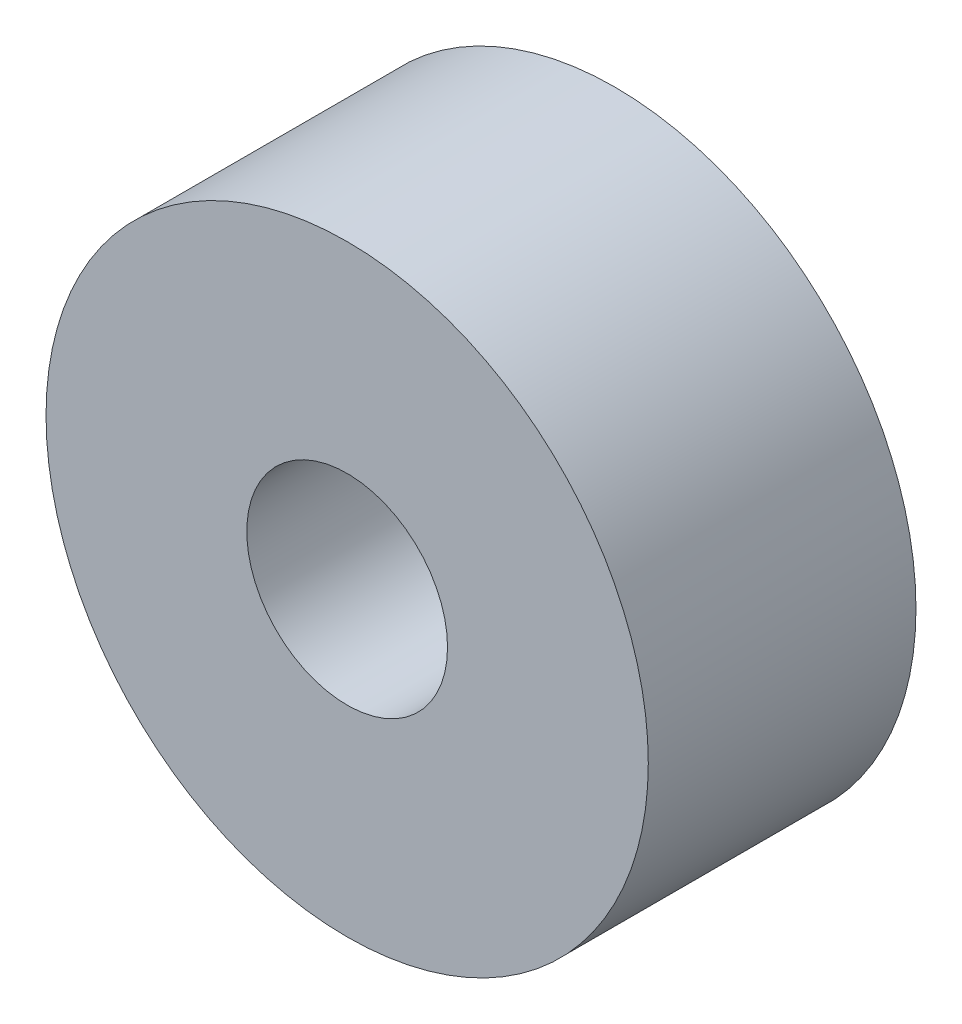
SolidWorks part; units mm, degrees
material "6061 合金"
ref_plane "前视基准面" through (0, 0, 0) normal (0, 0, 1) x (1, 0, 0)
ref_plane "上视基准面" through (0, 0, 0) normal (0, 1, 0) x (1, 0, 0)
ref_plane "右视基准面" through (0, 0, 0) normal (1, 0, 0) x (0, 0, -1)
sketch "草图1" plane through (0, 0, 0) normal (0, 0, 1) x (1, 0, 0)
  circle A0 centre (0, 0) radius 4.5
  circle A1 centre (0, 0) radius 1.5
  dimension "D1" = 3
  dimension "D2" = 9
extrude "凸台-拉伸1" add sketch "草图1" along normal mid plane 4
